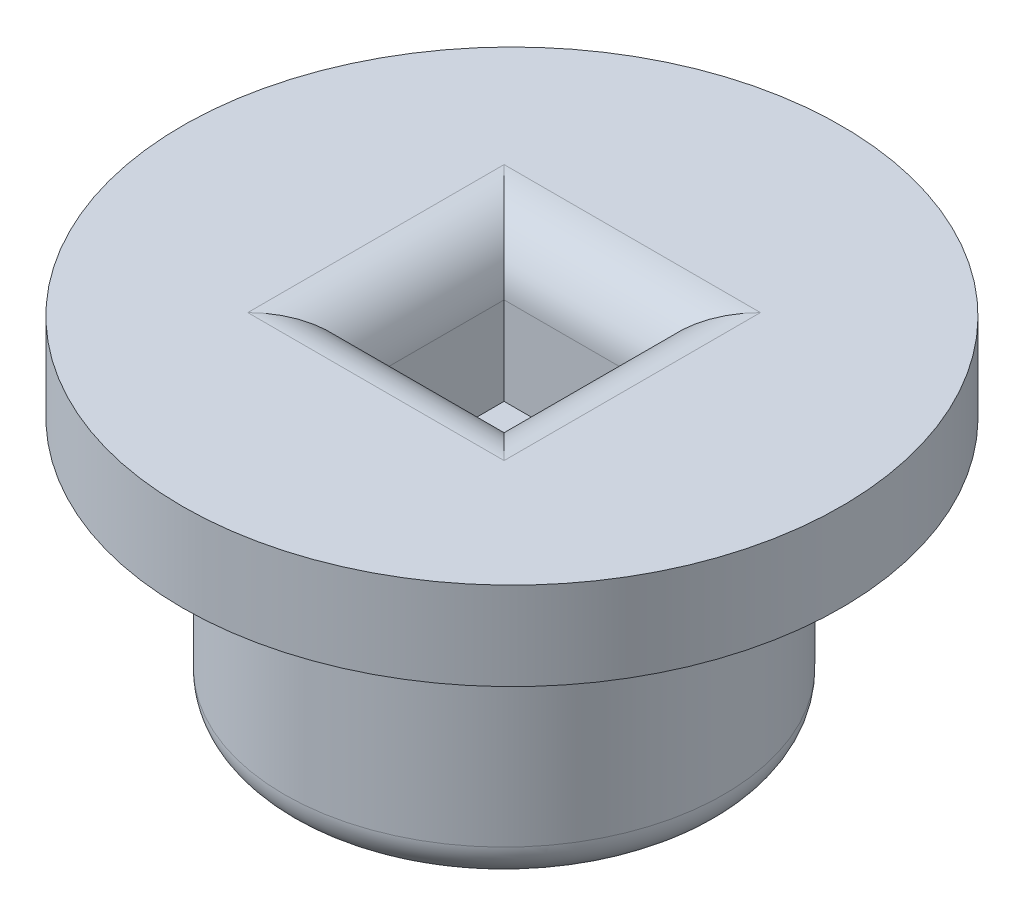
SolidWorks part; units mm, degrees
ref_plane "前视基准面" through (0, 0, 0) normal (0, 0, 1) x (1, 0, 0)
ref_plane "上视基准面" through (0, 0, 0) normal (0, 1, 0) x (1, 0, 0)
ref_plane "右视基准面" through (0, 0, 0) normal (1, 0, 0) x (0, 0, -1)
sketch "草图1" plane through (0, 0, 0) normal (0, 1, 0) x (1, 0, 0)
  circle A0 centre (0, 0) radius 3
  dimension "D1" = 6
extrude "凸台-拉伸1" add sketch "草图1" along normal blind 3.5 contours A0
sketch "草图2" plane through (0, 3.5, 0) normal (0, 1, 0) x (1, 0, 0)
  circle A0 centre (0.0949, 0.012) radius 4.5
  dimension "D1" = 9
extrude "凸台-拉伸2" add sketch "草图2" along normal blind 1.2
sketch "草图4" plane through (0, 4.7, 0) normal (0, 1, 0) x (1, 0, 0)
  line L1 (0.95, -0.95) -> (-0.95, -0.95)
  line L2 (0.95, -0.95) -> (0.95, 0.95)
  line L3 (0.95, 0.95) -> (-0.95, 0.95)
  line L4 (-0.95, -0.95) -> (-0.95, 0.95)
  line L5 (0.95, -0.95) -> (-0.95, 0.95) construction
  line L6 (0.95, 0.95) -> (-0.95, -0.95) construction
  circle A0 centre (0, 0) radius 3 construction
  point P0 (0, 0)
  dimension "D1" = 1.9
  dimension "D2" = 1.9
extrude "切除-拉伸1" cut sketch "草图4" against normal blind 2
fillet "圆角1" radius 0.5 1 edges at (0, 0, 3)
fillet "圆角2" radius 0.8 4 edges at (0, 4.7, 0.95) (-0.95, 4.7, 0) (0, 4.7, -0.95) (0.95, 4.7, 0)
